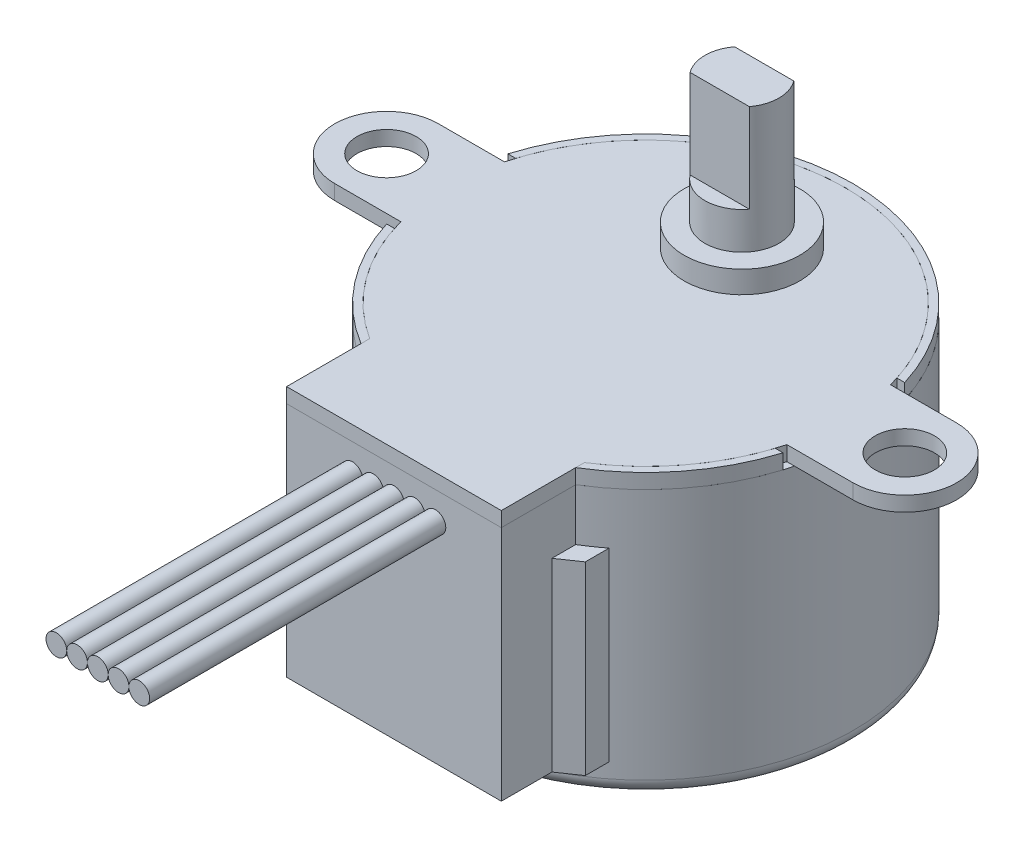
SolidWorks part; units mm, degrees
ref_plane "Front Plane" through (0, 0, 0) normal (0, 0, 1) x (1, 0, 0)
ref_plane "Top Plane" through (0, 0, 0) normal (0, 1, 0) x (1, 0, 0)
ref_plane "Right Plane" through (0, 0, 0) normal (1, 0, 0) x (0, 0, -1)
sketch "Sketch1" plane through (0, 0, 0) normal (0, 1, 0) x (1, 0, 0)
  circle A0 centre (0, 0) radius 14
  dimension "D1" = 28
extrude "Boss-Extrude1" add sketch "Sketch1" along normal blind 18
sketch "Sketch2" plane through (0, 18, 0) normal (0, 1, 0) x (1, 0, 0)
  line L0 (0, 16.9887) -> (0, 13.5) construction
  line L1 (13.0384, 3.5) -> (17.5, 3.5)
  line L2 (17.5, -3.5) -> (13.0384, -3.5)
  line L3 (-17.5, -3.5) -> (-13.0384, -3.5)
  line L4 (-13.0384, 3.5) -> (-17.5, 3.5)
  line L5 (-7.25, -11.388) -> (-7.25, -17)
  line L6 (-7.25, -17) -> (7.25, -17)
  line L7 (7.25, -11.388) -> (7.25, -17)
  line L8 (0, -11.5) -> (0, -20.5487) construction
  arc A0 (13.0384, 3.5) -> (-13.0384, 3.5) centre (0, 0) ccw
  circle A1 centre (17.5, 0) radius 2
  arc A2 (17.5, -3.5) -> (17.5, 3.5) centre (17.5, 0) ccw
  arc A3 (-17.5, -3.5) -> (-17.5, 3.5) centre (-17.5, 0) cw
  circle A4 centre (-17.5, 0) radius 2
  arc A5 (-13.0384, -3.5) -> (-7.25, -11.388) centre (0, 0) ccw
  arc A6 (7.25, -11.388) -> (13.0384, -3.5) centre (0, 0) ccw
  point P20 (0, -17)
  dimension "D1" = 27
  dimension "D3" = 4
  dimension "D2" = 17.5
  dimension "D4" = 3.5
  dimension "D5" = 7
  dimension "D6" = 17
  dimension "D7" = 7.25
extrude "Boss-Extrude2" add sketch "Sketch2" along normal blind 1 separate body
sketch "Sketch3" plane through (0, 18, 0) normal (0, 1, 0) x (1, 0, 0)
  line L0 (-13.3913, 4.0833) -> (-12.8675, 4.0838)
  line L3 (13.3835, -4.1087) -> (12.8596, -4.1087)
  line L5 (12.8596, 4.1087) -> (13.3834, 4.1092)
  line L6 (-12.8596, -4.1087) -> (-13.3835, -4.1087)
  line L7 (-7.25, -11.388) -> (-7.25, -11.9765)
  line L8 (-7.25, -11.388) -> (-7.25, -17) construction
  line L9 (7.25, -11.388) -> (7.25, -11.9765)
  line L10 (7.25, -17) -> (7.25, -11.388) construction
  arc A0 (-12.8596, -4.1087) -> (-7.25, -11.388) centre (0, 0) ccw
  circle A1 centre (0, 0) radius 14
  arc A2 (-13.3835, -4.1087) -> (-7.25, -11.9765) centre (0, 0) ccw
  arc A3 (12.8596, 4.1087) -> (-12.8675, 4.0838) centre (0, 0) ccw
  arc A4 (13.3834, 4.1092) -> (-13.3913, 4.0833) centre (0, 0) ccw
  arc A5 (7.25, -11.388) -> (12.8596, -4.1087) centre (0, 0) ccw
  arc A6 (7.25, -11.9765) -> (13.3835, -4.1087) centre (0, 0) ccw
  dimension "D1" = 0
extrude "Boss-Extrude3" add sketch "Sketch3" along normal blind 1 separate body
sketch "Sketch4" plane through (0, 19, 0) normal (0, 1, 0) x (1, 0, 0)
  line L11 (0, 0) -> (0, -6.5603) construction
  line L14 (7.25, -17) -> (-7.25, -17)
  line L15 (7.25, -17) -> (7.25, -13.5831)
  line L16 (-8.5852, -12.6652) -> (-7.25, -13.5831)
  line L17 (-8.5852, -11.0587) -> (-8.5852, -12.6652)
  line L19 (8.5852, -11.0587) -> (8.5852, -12.6652)
  line L21 (8.5852, -12.6652) -> (7.25, -13.5831)
  line L22 (-7.25, -13.5831) -> (-7.25, -17)
  arc A2 (7.25, -11.9765) -> (13.3835, -4.1087) centre (0, 0) ccw construction
  arc A3 (-8.5852, -11.0587) -> (8.5852, -11.0587) centre (0, 0) ccw
extrude "Boss-Extrude4" add sketch "Sketch4" against normal blind 16 from offset 1 separate body offset against normal yes
sketch "Schizzo1" plane through (0, 18, 0) normal (0, 1, 0) x (1, 0, 0)
  line L1 (-7.25, -13.5831) -> (-7.25, -11.9765)
  line L3 (7.25, -13.5831) -> (7.25, -11.9765)
  line L7 (7.25, -17) -> (7.25, -13.5831)
  line L8 (7.25, -13.5831) -> (8.5852, -12.6652)
  line L9 (8.5852, -12.6652) -> (8.5852, -11.0587)
  line L10 (-8.5852, -11.0587) -> (-8.5852, -12.6652)
  line L11 (-8.5852, -12.6652) -> (-7.25, -13.5831)
  line L12 (-7.25, -13.5831) -> (-7.25, -17)
  line L13 (-7.25, -17) -> (7.25, -17)
  line L15 (7.25, -13.5831) -> (8.5852, -12.6652)
  line L16 (8.5852, -12.6652) -> (8.5852, -11.0587)
  line L17 (-8.5852, -11.0587) -> (-8.5852, -12.6652)
  line L18 (-8.5852, -12.6652) -> (-7.25, -13.5831)
  arc A0 (7.25, -11.9765) -> (8.5852, -11.0587) centre (0, 0) ccw
  arc A1 (-8.5852, -11.0587) -> (8.5852, -11.0587) centre (0, 0) ccw
  arc A2 (-8.5852, -11.0587) -> (-7.25, -11.9765) centre (0, 0) ccw
  dimension "D1" = 0
extrude "Taglio-Estrusione1" cut sketch "Schizzo1" against normal blind 3.5
sketch "Sketch6" plane through (0, 19, 0) normal (0, 1, 0) x (1, 0, 0)
  circle A0 centre (0, 6.5) radius 3.9
  dimension "D2" = 7.8
  dimension "D1" = 6.5
extrude "Boss-Extrude6" add sketch "Sketch6" along normal blind 1.5 separate body
sketch "Sketch7" plane through (0, 20.5, 0) normal (0, 1, 0) x (1, 0, 0)
  circle A0 centre (0, 6.5) radius 2.5
  dimension "D1" = 5
extrude "Boss-Extrude7" add sketch "Sketch7" along normal blind 2.5 separate body
sketch "Sketch8" plane through (0, 23, 0) normal (0, 1, 0) x (1, 0, 0)
  line L0 (-2, 8) -> (2, 8)
  line L1 (-2, 5) -> (2, 5)
  arc A0 (2, 5) -> (2, 8) centre (0, 6.5) ccw
  circle A1 centre (0, 6.5) radius 2.5
  arc A2 (-2, 8) -> (-2, 5) centre (0, 6.5) ccw
  dimension "D2" = 1.5
  dimension "D3" = 1.5
  dimension "D1" = 0
extrude "Boss-Extrude8" add sketch "Sketch8" along normal blind 6
sketch "Sketch9" plane through (0, 0, 17) normal (0, 0, 1) x (1, 0, 0)
  line L1 (-7.25, 18) -> (7.25, 18) construction
  circle A0 centre (-2.8, 16.1282) radius 0.7
  point P4 (0, 18)
  dimension "D1" = 1.4
  dimension "D2" = 2.8
extrude "Boss-Extrude9" add sketch "Sketch9" along normal blind 20 separate body
pattern_linear "LPattern1" count 5 spacing 1.4 along (1, 0, 0) of bodies 112
fillet "Raccordo1" radius 1 1 edges at (0, 0, 14)
